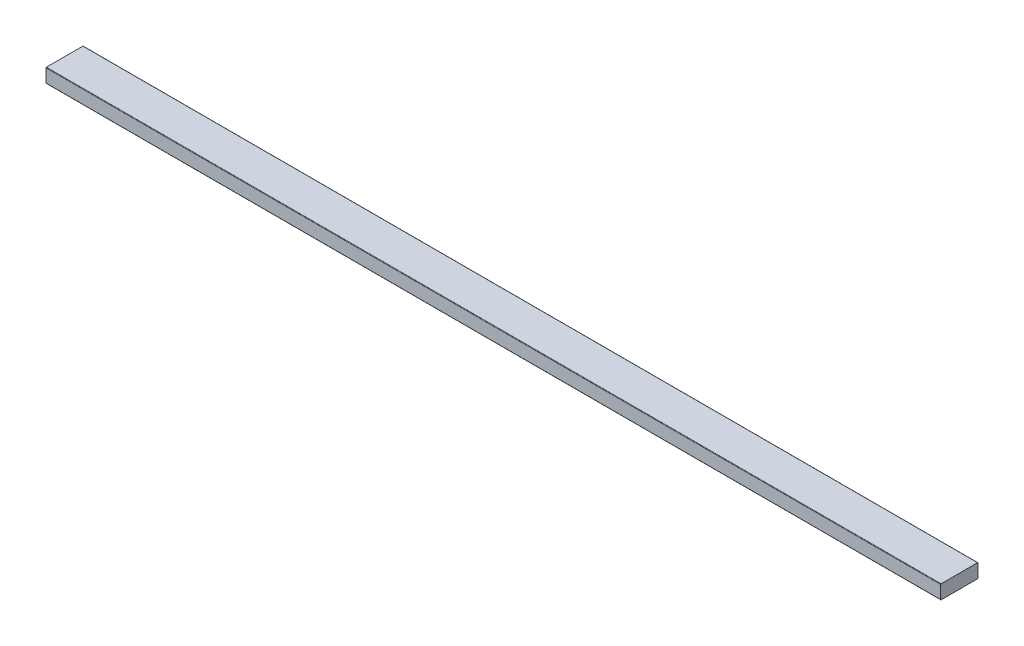
SolidWorks part; units mm, degrees
ref_plane "Front Plane" through (0, 0, 0) normal (0, 0, 1) x (1, 0, 0)
ref_plane "Top Plane" through (0, 0, 0) normal (0, 1, 0) x (1, 0, 0)
ref_plane "Right Plane" through (0, 0, 0) normal (1, 0, 0) x (0, 0, -1)
sketch "Sketch1" plane through (0, 0, 0) normal (0, 1, 0) x (1, 0, 0)
  line L1 (304.8, -12.7) -> (-304.8, -12.7)
  line L2 (304.8, -12.7) -> (304.8, 12.7)
  line L3 (304.8, 12.7) -> (-304.8, 12.7)
  line L4 (-304.8, -12.7) -> (-304.8, 12.7)
  line L5 (304.8, -12.7) -> (-304.8, 12.7) construction
  line L6 (304.8, 12.7) -> (-304.8, -12.7) construction
  point P0 (0, 0)
  dimension "Length" = 609.6
  dimension "Width" = 25.4
sketch "Sketch2" plane through (0, 0, 0) normal (1, 0, 0) x (0, 0, -1)
  line L0 (12.7, 4.7625) -> (12.7, -4.7625) construction
  point P2 (12.7, 0)
  dimension "Thickness" = 9.525
sketch "Sketch3" plane through (0, 0, 0) normal (0, 1, 0) x (1, 0, 0)
  line L1 (-304.8, 12.7) -> (304.8, 12.7)
  line L2 (-304.8, 12.7) -> (-304.8, -12.7)
  line L3 (-304.8, -12.7) -> (304.8, -12.7)
  line L4 (304.8, 12.7) -> (304.8, -12.7)
extrude "Boss-Extrude1" add sketch "Sketch3" against normal up to vertex (4.7625 mm away) and the other way up to vertex (4.7625 mm away) up to point (0, -4.7625, -12.7) other way up to point (0, 4.7625, -12.7)
fillet "Fillet1" radius 0.3143 4 edges at (0, -4.7625, 12.7) (0, -4.7625, -12.7) (0, 4.7625, -12.7) (0, 4.7625, 12.7)
equation "\"D1@Fillet1\" = \"Thickness@Sketch2\" * .033"
